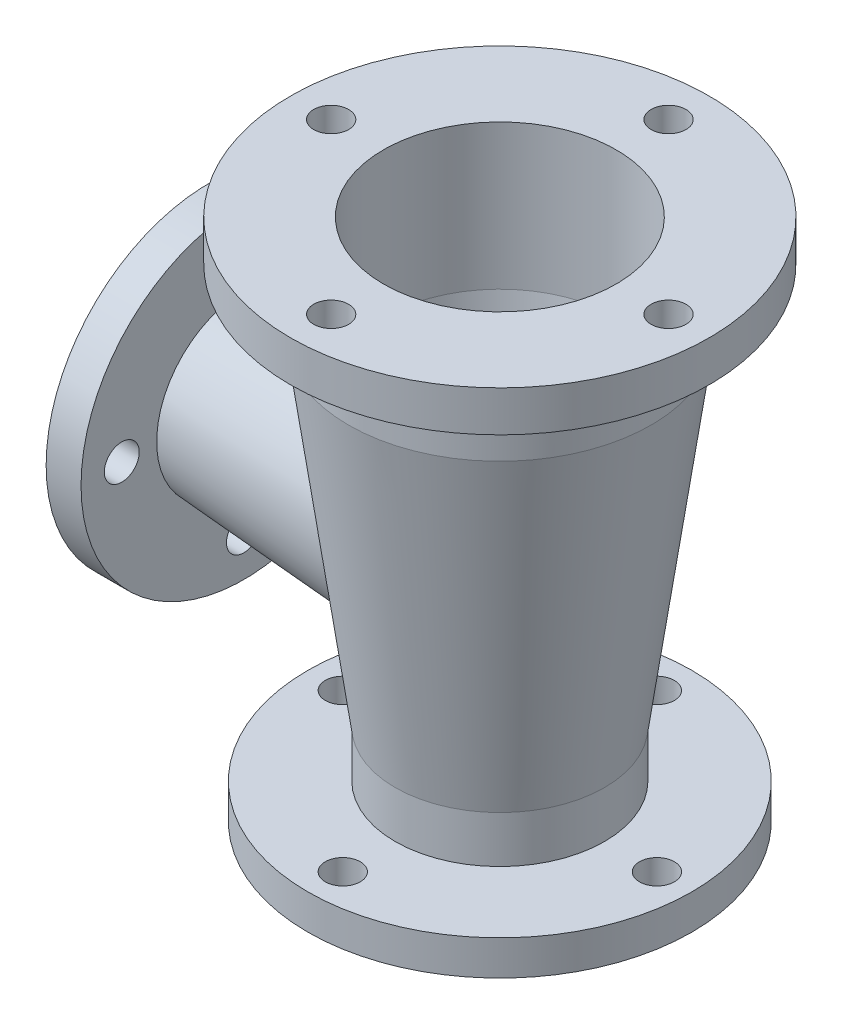
SolidWorks part; units mm, degrees
ref_plane "Front Plane" through (0, 0, 0) normal (0, 0, 1) x (1, 0, 0)
ref_plane "Top Plane" through (0, 0, 0) normal (0, 1, 0) x (1, 0, 0)
ref_plane "Right Plane" through (0, 0, 0) normal (1, 0, 0) x (0, 0, -1)
sketch "Sketch1" plane through (0, 0, 0) normal (0, 0, 1) x (1, 0, 0)
  line L0 (0, 125.2267) -> (0, -125.2267) construction
  line L1 (40, 125.2267) -> (72, 125.2267)
  line L2 (72, 125.2267) -> (72, 111.2267)
  line L3 (72, 111.2267) -> (52, 111.2267)
  line L4 (52, 111.2267) -> (52, 89.2267)
  line L5 (52, 89.2267) -> (36, -26.7059)
  line L9 (66, -42.7733) -> (36, -42.7733)
  line L12 (27.5957, -14.4568) -> (40, 75.422)
  line L13 (40, 75.422) -> (40, 125.2267)
  line L14 (22.6427, -18.7733) -> (20, -18.7733)
  line L15 (20, -18.7733) -> (20, -54.7733)
  line L16 (20, -54.7733) -> (66, -54.7733)
  line L17 (66, -54.7733) -> (66, -42.7733)
  line L18 (36, -26.7059) -> (36, -42.7733)
  arc A0 (27.5957, -14.4568) -> (22.6427, -18.7733) centre (22.6427, -13.7733) cw
  point P2 (20, -36.7733)
  point P9 (40, 15.2066)
  point P13 (27, -18.7733)
  point P14 (25.5167, 11.1344)
  point P16 (40, 37.8243)
  point P20 (10, -59.2324)
  point P21 (0, 69.0092)
  point P22 (-200.945, -2.6631)
  point P23 (27, 12.9817)
  point P25 (0, 0)
  point P26 (0, 0)
  point P27 (0, 0)
  point P28 (27.1731, 11.6285)
  point P29 (-6.1392, 7.2913)
  point P30 (27, 13.8489)
  point P31 (0, 0)
  point P32 (40, 12.1358)
  point P33 (-176.3481, -7.0568)
  point P34 (10, 12.6476)
  point P35 (52, 94.2911)
  point P36 (40, 84.3223)
  point P37 (72, 131.7589)
  point P38 (0, 0)
  point P39 (0, -125.2267)
  point P40 (0, 0)
  point P43 (27, -18.7733)
  dimension "D9" = 132
  dimension "D12" = 5
  dimension "D1" = 14
  dimension "D2" = 36
  dimension "D3" = 12
  dimension "D4" = 40
  dimension "D5" = 40
  dimension "D6" = 52
  dimension "D7" = 72
  dimension "D8" = 54
  dimension "D10" = 10
  dimension "D11" = 36
  dimension "D13" = 72
  dimension "D14" = 144
revolve "Revolve1" add sketch "Sketch1" angle 360 about L0
sketch "Sketch2" plane through (0, -42.7733, 0) normal (0, 1, 0) x (1, 0, 0)
  circle A0 centre (0, 0) radius 54 construction
  circle A1 centre (0, 54) radius 6
  circle A2 centre (54, 0) radius 6
  circle A3 centre (0, -54) radius 6
  circle A4 centre (-54, 0) radius 6
  point P5 (0, 0)
  point P14 (0, 0)
  dimension "D1" = 108
  dimension "D2" = 12
  dimension "D3" = 4
extrude "Cut-Extrude1" cut sketch "Sketch2" against normal blind 108 contours A1 | A4 | A2 | A3
sketch "Sketch3" plane through (0, 125.2267, 0) normal (0, 1, 0) x (1, 0, 0)
  circle A0 centre (0, 0) radius 58 construction
  circle A1 centre (0, 58) radius 6
  circle A2 centre (58, 0) radius 6
  circle A3 centre (0, -58) radius 6
  circle A4 centre (-58, 0) radius 6
  point P5 (0, 0)
  point P14 (0, 0)
  dimension "D1" = 116
  dimension "D2" = 12
  dimension "D3" = 4
extrude "Cut-Extrude2" cut sketch "Sketch3" against normal blind 108
sketch "Sketch4" plane through (0, 0, 0) normal (0, 0, 1) x (1, 0, 0)
  line L0 (0, 125.2267) -> (0, -54.7733) construction
  line L1 (6, 125.2267) -> (-6, 125.2267) construction
  line L2 (-66, -54.7733) -> (66, -54.7733) construction
  line L3 (-100, 29.2267) -> (83.6456, 29.2267) construction
  line L4 (64, 125.2267) -> (52, 125.2267) construction
  line L5 (-100, 29.2267) -> (-100, 85.2267)
  line L6 (-100, 85.2267) -> (-88, 85.2267)
  line L7 (-88, 85.2267) -> (-88, 59.2267)
  line L8 (-88, 59.2267) -> (0, 65.2267)
  line L9 (0, 65.2267) -> (0, 29.2267)
  line L10 (0, 29.2267) -> (-100, 29.2267)
  dimension "D1" = 96
  dimension "D2" = 56
  dimension "D3" = 100
  dimension "D4" = 12
  dimension "D5" = 30
  dimension "D6" = 36
revolve "Revolve2" add sketch "Sketch4" angle 360 about L10
sketch "Sketch5" plane through (0, 0, 0) normal (0, 0, 1) x (1, 0, 0)
  line L0 (0, 125.2267) -> (0, 111.2267) construction
  line L1 (6, 125.2267) -> (-6, 125.2267) construction
  line L3 (0, 111.2267) -> (40, 111.2267)
  line L10 (0, 111.2267) -> (0, -14.4568)
  line L13 (0, -14.4568) -> (27.5, -14.4568)
  line L14 (27.5957, -14.4568) -> (-27.5957, -14.4568) construction
  line L15 (27.5, -14.4568) -> (40, 75.422)
  line L16 (40, 75.422) -> (-40, 75.422) construction
  line L17 (40, 75.422) -> (40, 111.2267)
  point P7 (33.2546, 111.2267)
  point P17 (39.8159, 75.422)
  dimension "D1" = 40
  dimension "D2" = 27.5
revolve "Cut-Revolve2" cut sketch "Sketch5" angle 360 about L0
sketch "Sketch6" plane through (0, 0, 0) normal (0, 0, 1) x (1, 0, 0)
  line L0 (0, 125.2267) -> (0, -54.7733) construction
  line L1 (72, 125.2267) -> (-72, 125.2267) construction
  line L2 (-66, -54.7733) -> (66, -54.7733) construction
  line L3 (-100, 29.2267) -> (-100, 49.2267)
  line L4 (-100, 85.2267) -> (-100, -26.7733) construction
  line L5 (-100, 49.2267) -> (0, 55.2267)
  line L6 (0, 55.2267) -> (0, 29.2267)
  line L7 (0, 29.2267) -> (-100, 29.2267)
  point P10 (0, 57.6792)
  dimension "D1" = 20
  dimension "D2" = 26
revolve "Cut-Revolve3" cut sketch "Sketch6" angle 360 about L7
sketch "Sketch7" plane through (-100, 0, 0) normal (-1, 0, 0) x (0, 0, 1)
  line L0 (0, 85.2267) -> (0, -26.7733) construction
  circle A0 centre (0, 29.2267) radius 56 construction
  circle A1 centre (0, 29.2267) radius 42 construction
  circle A2 centre (0, 71.2267) radius 6
  circle A3 centre (42, 29.2267) radius 6
  circle A4 centre (0, -12.7733) radius 6
  circle A5 centre (-42, 29.2267) radius 6
  point P9 (0, 0)
  point P18 (0, 29.2267)
  dimension "D1" = 84
  dimension "D2" = 12
  dimension "D3" = 4
extrude "Cut-Extrude3" cut sketch "Sketch7" against normal blind 25
